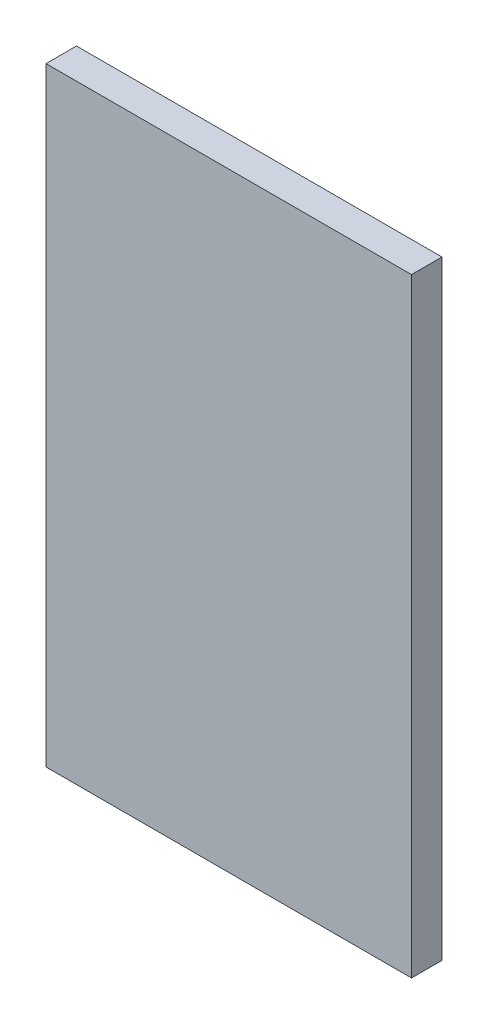
SolidWorks part; units mm, degrees
ref_plane "Front Plane" through (0, 0, 0) normal (0, 0, 1) x (1, 0, 0)
ref_plane "Top Plane" through (0, 0, 0) normal (0, 1, 0) x (1, 0, 0)
ref_plane "Right Plane" through (0, 0, 0) normal (1, 0, 0) x (0, 0, -1)
sketch "Sketch1" plane through (0, 0, 0) normal (0, 0, 1) x (1, 0, 0)
  line L1 (-81.1024, 118.8976) -> (38.8976, 118.8976)
  line L2 (-81.1024, 118.8976) -> (-81.1024, -81.1024)
  line L3 (-81.1024, -81.1024) -> (38.8976, -81.1024)
  line L4 (38.8976, 118.8976) -> (38.8976, -81.1024)
  dimension "D1" = 200
  dimension "D2" = 120
extrude "Boss-Extrude1" add sketch "Sketch1" along normal blind 10
